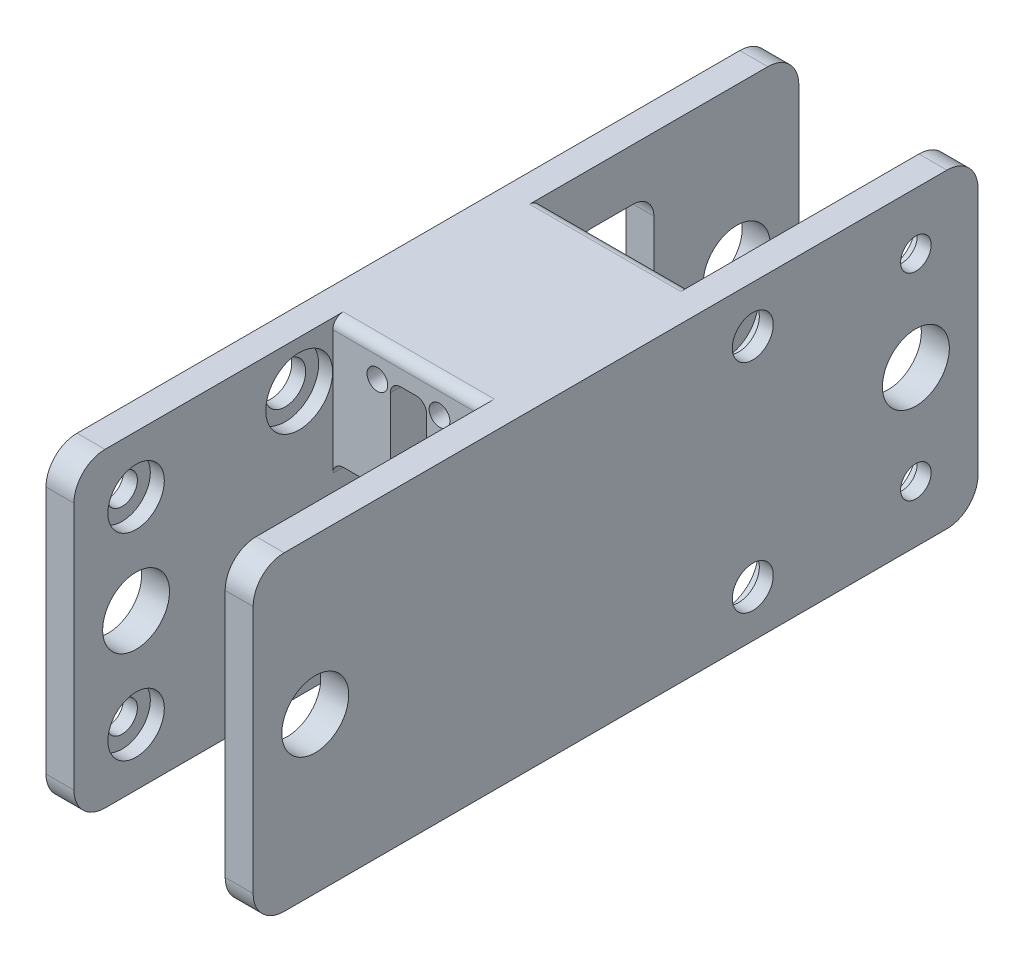
SolidWorks part; units mm, degrees
ref_plane "Front Plane" through (0, 0, 0) normal (0, 0, 1) x (1, 0, 0)
ref_plane "Top Plane" through (0, 0, 0) normal (0, 1, 0) x (1, 0, 0)
ref_plane "Right Plane" through (0, 0, 0) normal (1, 0, 0) x (0, 0, -1)
sketch "Sketch1" plane through (0, 0, 0) normal (0, 1, 0) x (1, 0, 0)
  line L0 (10, 5) -> (14, 5)
  line L1 (-10, -10) -> (10, -10)
  line L2 (-10, -10) -> (-10, 10)
  line L3 (-10, 10) -> (10, 10)
  line L4 (10, -10) -> (10, 10)
  line L5 (-10, -10) -> (10, 10) construction
  line L6 (-10, 10) -> (10, -10) construction
  line L7 (14, 5) -> (14, 3)
  line L8 (14, 3) -> (13, 3)
  line L9 (13, 3) -> (13, 4)
  line L10 (13, 4) -> (10, 4)
  line L11 (10, 4) -> (10, 5)
  line L19 (0, 10) -> (0, -10) construction
  point P0 (0, 0)
  dimension "D1" = 20
  dimension "D2" = 20
  dimension "D3" = 4
  dimension "D4" = 2
  dimension "D5" = 1
  dimension "D6" = 1
  dimension "D7" = 5
extrude "Boss-Extrude3" add sketch "Sketch1" along normal blind 30 contours L1 L4 L3 L2
sketch "Sketch10" plane through (0, 0, -10) normal (0, 0, -1) x (-1, 0, 0)
  line L0 (0, 30) -> (0, 0) construction
  line L1 (-1.75, 27.5) -> (1.75, 27.5)
  line L2 (10, 30) -> (-10, 30) construction
  line L11 (-10, 15) -> (10, 15) construction
  line L12 (-10, 30) -> (-10, 0) construction
  line L13 (10, 30) -> (10, 0) construction
  line L14 (1.75, 27.5) -> (1.75, 18)
  line L15 (1.75, 18) -> (7.3, 18)
  line L16 (7.3, 18) -> (7.3, 12)
  line L18 (-7.3, 18) -> (-7.3, 12)
  line L19 (-1.75, 18) -> (-7.3, 18)
  line L20 (-1.75, 27.5) -> (-1.75, 18)
  line L21 (-1.75, 2.5) -> (-1.75, 12)
  line L22 (-1.75, 12) -> (-7.3, 12)
  line L23 (1.75, 12) -> (7.3, 12)
  line L24 (1.75, 2.5) -> (1.75, 12)
  line L25 (-1.75, 2.5) -> (1.75, 2.5)
  circle A0 centre (-5.88, 19.86) radius 0.86
  circle A1 centre (-5.92, 9.33) radius 0.86
  point P10 (0, 15)
  point P21 (0, 27.5)
  point P24 (-7.3, 15)
  point P25 (7.3, 15)
  point P27 (0, 2.5)
  dimension "D5" = 1.72
  dimension "D6" = 4.86
  dimension "D7" = 1.72
  dimension "D9" = 5.92
  dimension "D1" = 2.5
  dimension "D2" = 1.75
  dimension "D3" = 3
  dimension "D4" = 2.7
  dimension "D8" = 5.88
  dimension "D11" = 5.67
extrude "Cut-Extrude11" cut sketch "Sketch10" against normal up to next
fillet "Fillet4" radius 1 12 edges at (-1.75, 18, 0) (-7.3, 18, 0) (-7.3, 12, 0) (-1.75, 12, 0) (-1.75, 2.5, 0) (1.75, 2.5, 0) (1.75, 12, 0) (7.3, 12, 0) (7.3, 18, 0) (1.75, 18, 0) (-1.75, 27.5, 0) (1.75, 27.5, 0)
sketch "Sketch12" plane through (0, 0, 10) normal (0, 0, 1) x (1, 0, 0)
  line L0 (-10, 15) -> (10, 15) construction
  line L1 (-10, 30) -> (-10, 0) construction
  line L2 (10, 30) -> (10, 0) construction
  line L21 (-7.3, 0) -> (-10, 0)
  line L22 (-7.3, 0) -> (-7.3, 30)
  line L23 (-7.3, 30) -> (-10, 30)
  line L24 (-10, 0) -> (-10, 30)
  line L25 (-7.3, 0) -> (-10, 30) construction
  line L26 (-7.3, 30) -> (-10, 0) construction
  point P4 (-8.65, 15)
  dimension "D1" = 2.7
extrude "Boss-Extrude13" add sketch "Sketch12" along normal blind 25
sketch "Sketch14" plane through (-7.3, 0, 0) normal (1, 0, 0) x (0, 0, -1)
  line L0 (-35, 15) -> (-10, 15) construction
  line L10 (-35, 0) -> (-35, 30) construction
  line L11 (-10, 30) -> (-10, 0) construction
  circle A0 centre (-29, 15) radius 3.23
  dimension "D4" = 6.46
  dimension "D1" = 6
extrude "Cut-Extrude13" cut sketch "Sketch14" against normal up to next
fillet "Fillet6" radius 3 2 edges at (-8.65, 30, 35) (-8.65, 0, 35)
sketch "Sketch16" plane through (0, 0, -10) normal (0, 0, -1) x (-1, 0, 0)
  line L0 (-10, 15) -> (10, 15) construction
  line L1 (-10, 30) -> (-10, 0) construction
  line L2 (10, 30) -> (10, 0) construction
  line L3 (10, 30) -> (-10, 30) construction
  line L8 (7.3, 0) -> (10, 0)
  line L9 (7.3, 0) -> (7.3, 30)
  line L10 (7.3, 30) -> (10, 30)
  line L11 (10, 0) -> (10, 30)
  line L12 (7.3, 0) -> (10, 30) construction
  line L13 (7.3, 30) -> (10, 0) construction
  point P6 (8.65, 15)
  dimension "D1" = 2.7
extrude "Boss-Extrude14" add sketch "Sketch16" along normal blind 25
sketch "Sketch17" plane through (-7.3, 0, 0) normal (1, 0, 0) x (0, 0, -1)
  line L0 (35, 15) -> (10, 15) construction
  line L1 (35, 30) -> (35, 0) construction
  line L2 (10, 30) -> (10, 0) construction
  circle A0 centre (29, 15) radius 3.23
  dimension "D1" = 6.46
  dimension "D2" = 6
extrude "Cut-Extrude14" cut sketch "Sketch17" against normal up to next
fillet "Fillet11" radius 3 2 edges at (-8.65, 30, -35) (-8.65, 0, -35)
mirror "Mirror1" about plane through (0, 0, 0) normal (1, 0, 0) of "Boss-Extrude13", "Boss-Extrude14", "Cut-Extrude13", "Fillet6", "Fillet11", "Cut-Extrude14"
fillet "Fillet12" radius 1 4 edges at (0, 30, -10) (0, 0, -10) (0, 30, 10) (0, 0, 10)
sketch "Sketch18" plane through (0, 0, -10) normal (0, 0, -1) x (-1, 0, 0)
  line L0 (0, 29) -> (0, 1) construction
  line L1 (7.3, 29) -> (-7.3, 29) construction
  line L4 (-7.3, 1) -> (7.3, 1) construction
  circle A0 centre (-3, 27) radius 1
  circle A1 centre (3, 3) radius 1
  dimension "D1" = 2
  dimension "D2" = 2
  dimension "D3" = 3
  dimension "D4" = 2
  dimension "D5" = 3
  dimension "D6" = 2
extrude "Cut-Extrude15" cut sketch "Sketch18" against normal up to next
mirror "Mirror2" about plane through (0, 0, 0) normal (1, 0, 0) of "Cut-Extrude15"
sketch "Sketch20" plane through (7.3, 0, 0) normal (-1, 0, 0) x (0, 0, 1)
  line L0 (-32, 30) -> (-9, 30) construction
  line L1 (-10, 29) -> (-10, 17) construction
  line L2 (-10, 15) -> (-35, 15) construction
  line L3 (-35, 27) -> (-35, 3) construction
  line L4 (-32, 0) -> (-9, 0) construction
  line L5 (-10, 17) -> (-10, 13) construction
  circle A0 centre (-13.25, 25.48) radius 1.98
  circle A1 centre (-13.25, 4.52) radius 1.98
  circle A2 centre (-29, 5.48) radius 1.475
  circle A3 centre (-29, 24.52) radius 1.475
  dimension "D1" = 3.96
  dimension "D2" = 4.52
  dimension "D3" = 3.25
  dimension "D4" = 2.95
  dimension "D5" = 5.48
  dimension "D6" = 6
extrude "Cut-Extrude16" cut sketch "Sketch20" against normal up to next
sketch "Sketch21" plane through (-7.3, 0, 7.3) normal (-1, 0, 0) x (0, 0, 1)
  line L0 (24.7, 0) -> (1.7, 0) construction
  line L1 (2.7, 17) -> (2.7, 13) construction
  line L2 (27.7, 15) -> (2.7, 15) construction
  line L5 (27.7, 3) -> (27.7, 27) construction
  line L6 (2.7, 1) -> (2.7, 13) construction
  circle A0 centre (5.95, 25.48) radius 1.98
  circle A1 centre (5.95, 4.52) radius 1.98
  circle A2 centre (21.7, 5.48) radius 1.475
  circle A3 centre (21.7, 24.52) radius 1.475
  dimension "D1" = 3.96
  dimension "D2" = 3.25
  dimension "D3" = 4.52
  dimension "D4" = 2.95
  dimension "D5" = 6
  dimension "D6" = 5.48
extrude "Cut-Extrude17" cut sketch "Sketch21" along normal up to next
sketch "Sketch22" plane through (7.3, 0, 0) normal (-1, 0, 0) x (0, 0, 1)
  line L0 (-10, 17) -> (-10, 13) construction
  line L1 (10, 17) -> (-10, 17) construction
  line L2 (-35, 15) -> (-10, 15) construction
  line L3 (-35, 27) -> (-35, 3) construction
  circle A0 centre (-29, 24.52) radius 2.725
  circle A1 centre (-29, 24.52) radius 1.475 construction
  circle A2 centre (-13.25, 25.48) radius 3.23
  circle A3 centre (-13.25, 25.48) radius 1.98 construction
  circle A4 centre (-13.25, 4.52) radius 3.23
  circle A5 centre (-29, 5.48) radius 2.725
  dimension "D1" = 1.25
  dimension "D2" = 1.25
extrude "Cut-Extrude18" cut sketch "Sketch22" against normal blind 1.35
sketch "Sketch23" plane through (-7.3, 0, 0) normal (1, 0, 0) x (0, 0, -1)
  line L0 (-10, 17) -> (-10, 13) construction
  line L1 (-10, 15) -> (-35, 15) construction
  line L2 (-35, 3) -> (-35, 27) construction
  circle A0 centre (-29, 24.52) radius 2.725
  circle A1 centre (-29, 24.52) radius 1.475 construction
  circle A2 centre (-13.25, 25.48) radius 3.23
  circle A3 centre (-13.25, 25.48) radius 1.98 construction
  circle A4 centre (-29, 5.48) radius 2.725
  circle A5 centre (-13.25, 4.52) radius 3.23
  dimension "D1" = 1.25
  dimension "D2" = 1.25
extrude "Cut-Extrude19" cut sketch "Sketch23" against normal blind 1.35
sketch "Sketch24" plane through (-10, 0, 0) normal (-1, 0, 0) x (0, 0, 1)
  line L0 (-17, 30) -> (-17, 0) construction
  line L1 (32, 30) -> (-32, 30) construction
  line L2 (32, 0) -> (-32, 0) construction
  line L3 (-35, 3) -> (-35, 27) construction
  line L4 (-21, 5) -> (-13, 5)
  line L5 (-21, 5) -> (-21, 25)
  line L6 (-21, 25) -> (-13, 25)
  line L7 (-13, 5) -> (-13, 25)
  line L8 (-21, 5) -> (-13, 25) construction
  line L9 (-21, 25) -> (-13, 5) construction
  point P6 (-17, 15)
  point P13 (-22.6122, 25)
  point P14 (-20, 15)
  point P15 (-17.3878, 25)
  point P16 (-20, 15)
  point P17 (-16.0485, 26.9928)
  dimension "D1" = 20
  dimension "D2" = 8
  dimension "D3" = 18
extrude "Cut-Extrude20" cut sketch "Sketch24" against normal up to next
fillet "Fillet13" radius 2 4 edges at (-8.65, 5, -13) (-8.65, 5, -21) (-8.65, 25, -21) (-8.65, 25, -13)
